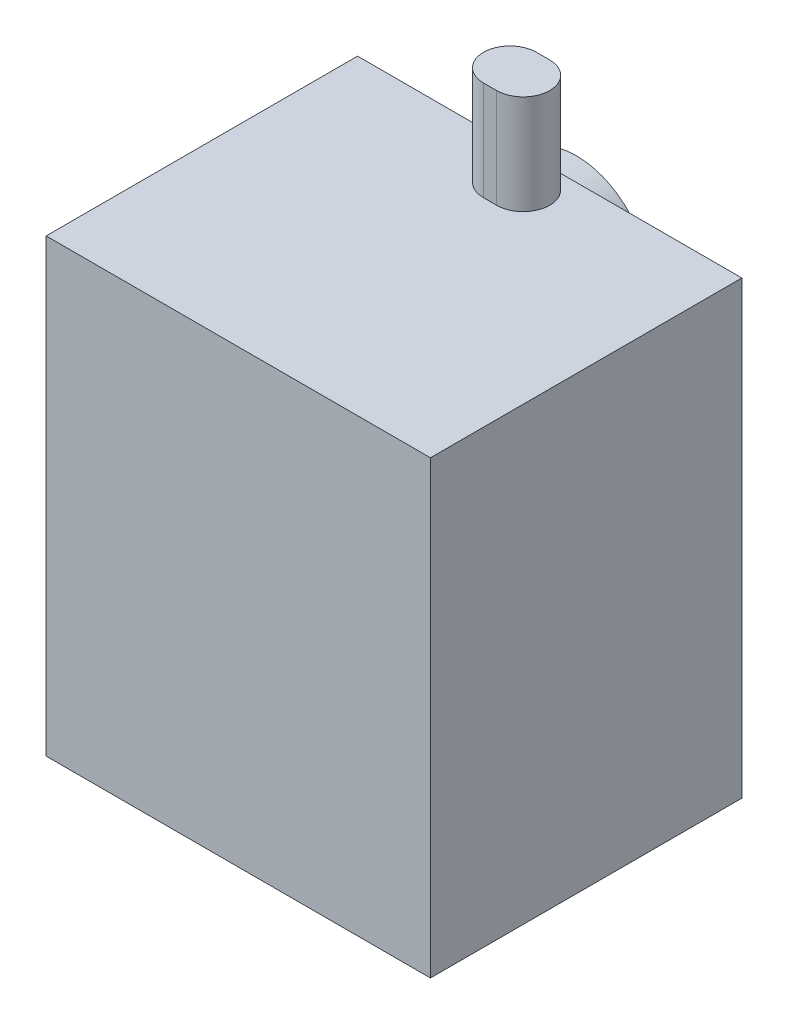
SolidWorks part; units mm, degrees
ref_plane "Plano frontal" through (0, 0, 0) normal (0, 0, 1) x (1, 0, 0)
ref_plane "Plano superior" through (0, 0, 0) normal (0, 1, 0) x (1, 0, 0)
ref_plane "Plano direito" through (0, 0, 0) normal (1, 0, 0) x (0, 0, -1)
sketch "Esboço1" plane through (0, 0, 0) normal (0, 0, 1) x (1, 0, 0)
  line L1 (29, -34) -> (-29, -34)
  line L2 (29, -34) -> (29, 34)
  line L3 (29, 34) -> (-29, 34)
  line L4 (-29, -34) -> (-29, 34)
  line L5 (29, -34) -> (-29, 34) construction
  line L6 (29, 34) -> (-29, -34) construction
  point P0 (0, 0)
  dimension "D1" = 58
  dimension "D2" = 68
extrude "Ressalto-extrusão1" add sketch "Esboço1" along normal mid plane 47
sketch "Esboço2" plane through (0, 0, -23.5) normal (0, 0, -1) x (-1, 0, 0)
  line L0 (9, -34) -> (9, 34) construction
  line L1 (-29, 34) -> (29, 34) construction
  line L2 (29, -34) -> (-29, -34) construction
  line L3 (29, 34) -> (29, -34) construction
  text T0 "BMS está aqui"
  dimension "D1" = 20
extrude "Corte-extrusão1" cut sketch "Esboço2" against normal blind 1
sketch "Esboço3" plane through (5, 34, 0) normal (0, -1, 0) x (0, 0, 1)
  line L0 (0, 5) -> (-23.5, 5) construction
  line L2 (-18.5, 4) -> (-18.5, 6) construction
  line L3 (-22.5, 4) -> (-22.5, 6)
  line L4 (-14.5, 4) -> (-14.5, 6)
  line L5 (-23.5, 34) -> (-23.5, -24) construction
  arc A0 (-22.5, 4) -> (-14.5, 4) centre (-18.5, 4) ccw
  arc A1 (-14.5, 6) -> (-22.5, 6) centre (-18.5, 6) ccw
  point P3 (-23.5, 0.0001)
  point P7 (-18.5, 5)
  point P12 (0, 0)
  point P13 (0, 0)
  point P15 (0, -0.691)
  point P16 (-23.5, 5)
  point P17 (0, 5)
  dimension "D1" = 4
  dimension "D2" = 2
  dimension "D3" = 1
extrude "Ressalto-extrusão2" add sketch "Esboço3" against normal blind 15
sketch "Esboço4" plane through (0, 0, -23.5) normal (0, 0, -1) x (-1, 0, 0)
  line L0 (0, 34) -> (0, 22.5) construction
  line L1 (-29, 34) -> (29, 34) construction
  circle A0 centre (0, 22.5) radius 11
  dimension "D1" = 22
  dimension "D2" = 11.5
extrude "Ressalto-extrusão3" add sketch "Esboço4" along normal blind 4
